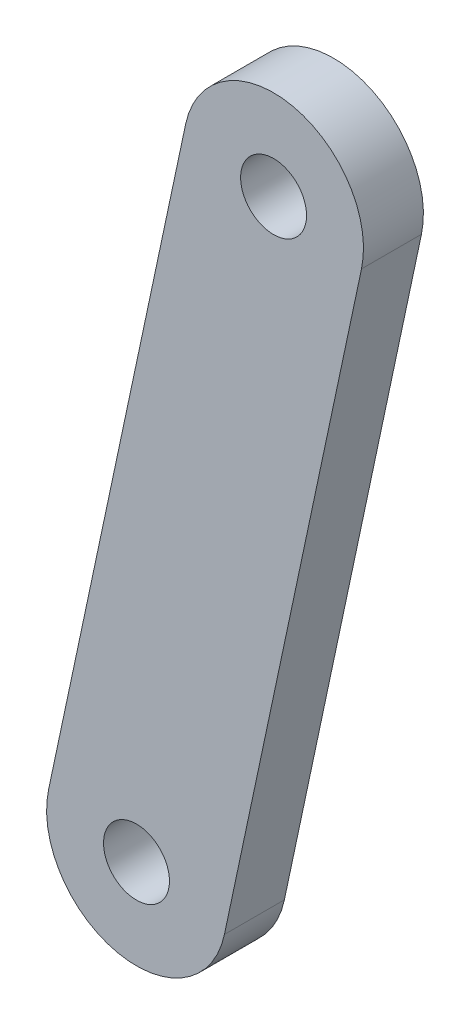
SolidWorks part; units mm, degrees
ref_plane "Спереди" through (0, 0, 0) normal (0, 0, 1) x (1, 0, 0)
ref_plane "Сверху" through (0, 0, 0) normal (0, 1, 0) x (1, 0, 0)
ref_plane "Справа" through (0, 0, 0) normal (1, 0, 0) x (0, 0, -1)
other "Configuration Table"
sketch "Eskiz_kontur" plane through (0, 0, 0) normal (0, 0, 1) x (1, 0, 0)
  line L0 (17.2628, 53.3433) -> (10.4017, 21.0644)
  line L1 (1.5983, 22.9356) -> (8.4594, 55.2145)
  arc A0 (8.4594, 55.2145) -> (17.2628, 53.3433) centre (12.8611, 54.2789) cw
  arc A1 (10.4017, 21.0644) -> (1.5983, 22.9356) centre (6, 22) cw
extrude "Plastina" add sketch "Eskiz_kontur" along normal blind 3
sketch "Eskiz_otverstiya" plane through (0, 0, 0) normal (0, 0, 1) x (1, 0, 0)
  circle A0 centre (6, 22) radius 1.65
  circle A1 centre (12.8611, 54.2789) radius 1.65
  dimension "d1" = 3.3
  dimension "d2" = 3.3
extrude "Otverstiya" cut sketch "Eskiz_otverstiya" against normal through all and the other way through all
equation "\"T3\" = 3"
equation "\"T5\" = 5"
equation "\"D_M3\" = 3.3"
equation "\"D_M2\" = 2.2"
equation "\"D_M3_TAP\" = 2.5"
equation "\"D_M4\" = 4.5"
equation "\"L1\" = 100"
equation "\"L2\" = 100"
equation "\"D1@Plastina\" = \"T3\""
equation "\"d1@Eskiz_otverstiya\" = \"D_M3\""
equation "\"d2@Eskiz_otverstiya\" = \"D_M3\""
